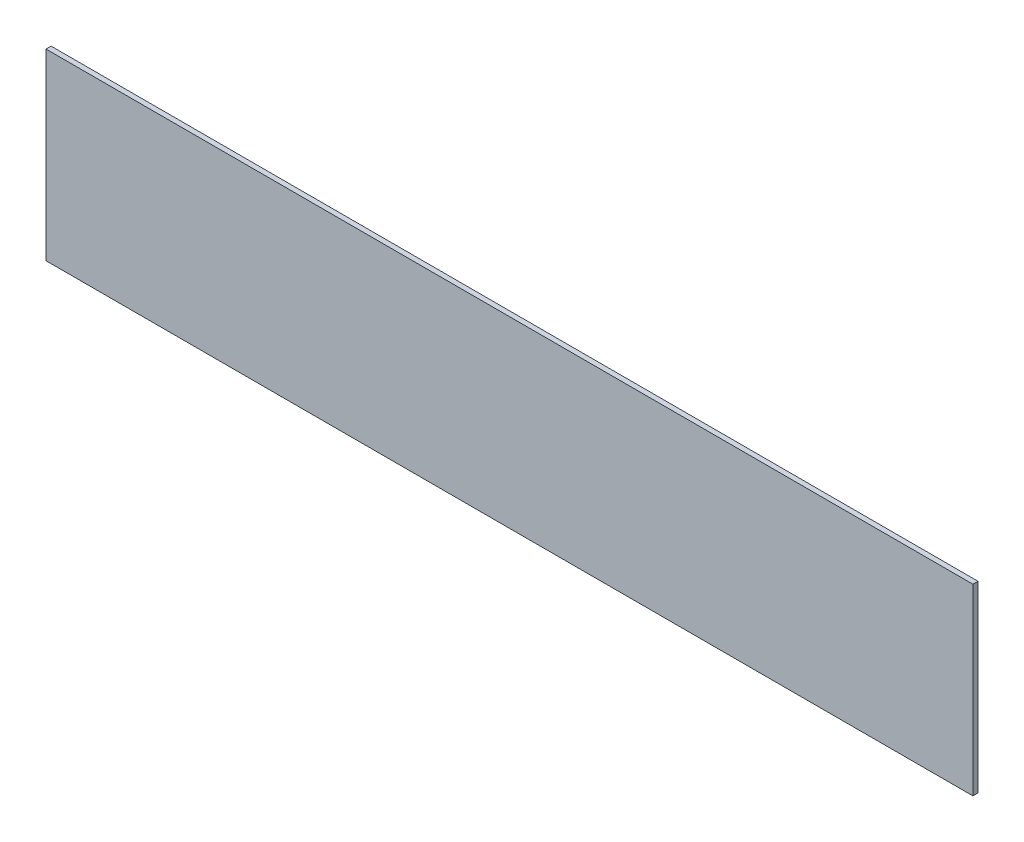
SolidWorks part; units mm, degrees
ref_plane "Front Plane" through (0, 0, 0) normal (0, 0, 1) x (1, 0, 0)
ref_plane "Top Plane" through (0, 0, 0) normal (0, 1, 0) x (1, 0, 0)
ref_plane "Right Plane" through (0, 0, 0) normal (1, 0, 0) x (0, 0, -1)
other "Configuration Table"
sketch "Sketch1" plane through (0, 0, 0) normal (0, 0, 1) x (1, 0, 0)
  line L1 (287, 623) -> (469, 623)
  line L2 (287, 623) -> (287, 659)
  line L3 (287, 659) -> (469, 659)
  line L4 (469, 623) -> (469, 659)
extrude "STORE_klape_kaset_kati_kulp_cukuru_1" add sketch "Sketch1" along normal blind 1 from offset 26 separate body
